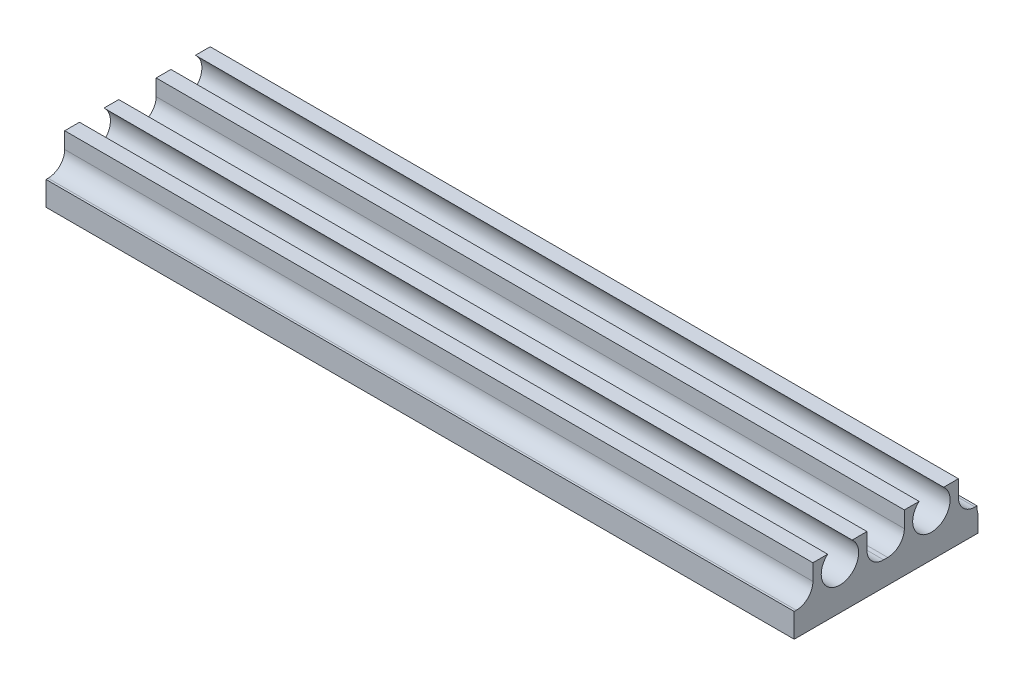
SolidWorks part; units mm, degrees
ref_plane "Спереди" through (0, 0, 0) normal (0, 0, 1) x (1, 0, 0)
ref_plane "Сверху" through (0, 0, 0) normal (0, 1, 0) x (1, 0, 0)
ref_plane "Справа" through (0, 0, 0) normal (1, 0, 0) x (0, 0, -1)
ref_plane "Плоскость4" through (90, 0, 0) normal (1, 0, 0) x (0, 0, -1)
sketch "Эскиз1" plane through (90, 0, 0) normal (1, 0, 0) x (0, 0, -1)
  line L0 (6.75, -24.0938) -> (6.75, 19.25)
  line L1 (6.75, 19.25) -> (-11.5938, 19.25)
  line L2 (-11.5938, 16.75) -> (-11, 16.75)
  line L3 (-11, 16.75) -> (-11, -16.75)
  line L4 (-11, -16.75) -> (-11.5938, -16.75)
  line L5 (-11.5938, -19.25) -> (-11, -19.25)
  line L6 (-11, -19.25) -> (-11, -23.5)
  line L7 (-11, -23.5) -> (-6.75, -23.5)
  line L8 (-6.75, -23.5) -> (-6.75, -24.0938)
  line L9 (-4.25, -24.0938) -> (-4.25, -23.5)
  line L10 (-4.25, -23.5) -> (4.25, -23.5)
  line L11 (4.25, -23.5) -> (4.25, -24.0938)
  arc A0 (-11.5938, 19.25) -> (-11.5938, 16.75) centre (-13.25, 18) ccw
  arc A1 (-11.5938, -16.75) -> (-11.5938, -19.25) centre (-13.25, -18) ccw
  arc A2 (-6.75, -24.0938) -> (-4.25, -24.0938) centre (-5.5, -25.75) ccw
  arc A3 (4.25, -24.0938) -> (6.75, -24.0938) centre (5.5, -25.75) ccw
extrude "Бобышка-Вытянуть1" add sketch "Эскиз1" against normal blind 90
sketch "Эскиз2" plane through (0, 19.25, 0) normal (0, 1, 0) x (-1, 0, 0)
  line L0 (-90, -6.75) -> (-90, 11)
  line L1 (-90, 11) -> (0, 11)
  line L2 (0, 11) -> (0, -6.75)
  line L3 (0, -6.75) -> (-90, -6.75)
extrude "Бобышка-Вытянуть2" add sketch "Эскиз2" along normal blind 8.2
sketch "Эскиз3" plane through (0, 0, -6.75) normal (0, 0, -1) x (-1, 0, 0)
  line L0 (0, -23.5) -> (-90, -23.5)
  line L1 (-90, -23.5) -> (-90, 27.45)
  line L2 (-90, 27.45) -> (0, 27.45)
  line L3 (0, 27.45) -> (0, -23.5)
extrude "Бобышка-Вытянуть3" add sketch "Эскиз3" along normal blind 8.2
sketch "Эскиз4" plane through (0, 0, 0) normal (-1, 0, 0) x (0, 0, 1)
  line L0 (-14.95, -14.75) -> (-11, -14.75)
  line L1 (-11, -14.75) -> (-11, 14.75)
  line L2 (-11, 14.75) -> (-14.95, 14.75)
  line L3 (-14.95, 14.75) -> (-14.95, -14.75)
extrude "Вырез-Вытянуть1" cut sketch "Эскиз4" against normal through all
sketch "Эскиз5" plane through (0, 0, 0) normal (-1, 0, 0) x (0, 0, 1)
  line L0 (-14.95, 27.45) -> (-14.95, 21.25)
  line L1 (-14.95, 21.25) -> (-11, 21.25)
  line L2 (-11, 21.25) -> (-11, 27.45)
  line L3 (-11, 27.45) -> (-14.95, 27.45)
extrude "Вырез-Вытянуть2" cut sketch "Эскиз5" against normal through all
sketch "Эскиз6" plane through (0, 0, 0) normal (-1, 0, 0) x (0, 0, 1)
  line L0 (-11, 27.45) -> (-11, 23.5)
  line L1 (-11, 23.5) -> (-8.75, 23.5)
  line L2 (-8.75, 23.5) -> (-8.75, 27.45)
  line L3 (-8.75, 27.45) -> (-11, 27.45)
extrude "Вырез-Вытянуть3" cut sketch "Эскиз6" against normal through all
sketch "Эскиз7" plane through (0, 0, 0) normal (-1, 0, 0) x (0, 0, 1)
  line L0 (-2.25, 27.45) -> (-2.25, 23.5)
  line L1 (-2.25, 23.5) -> (2.25, 23.5)
  line L2 (2.25, 23.5) -> (2.25, 27.45)
  line L3 (2.25, 27.45) -> (-2.25, 27.45)
extrude "Вырез-Вытянуть4" cut sketch "Эскиз7" against normal through all
sketch "Эскиз8" plane through (0, 0, 0) normal (-1, 0, 0) x (0, 0, 1)
  line L0 (11, 27.45) -> (8.75, 27.45)
  line L1 (8.75, 27.45) -> (8.75, 23.5)
  line L2 (8.75, 23.5) -> (11, 23.5)
  line L3 (11, 23.5) -> (11, 27.45)
extrude "Вырез-Вытянуть5" cut sketch "Эскиз8" against normal through all
sketch "Эскиз9" plane through (0, 0, 0) normal (-1, 0, 0) x (0, 0, 1)
  line L0 (-14.95, -23.5) -> (-11, -23.5)
  line L1 (-11, -23.5) -> (-11, -21.25)
  line L2 (-11, -21.25) -> (-14.95, -21.25)
  line L3 (-14.95, -21.25) -> (-14.95, -23.5)
extrude "Вырез-Вытянуть6" cut sketch "Эскиз9" against normal through all
sketch "Эскиз10" plane through (90, 0, 0) normal (1, 0, 0) x (0, 0, -1)
  line L0 (10.1, 22.6) -> (-10.1, 22.6)
  line L1 (-10.1, 22.6) -> (-10.1, -22.6)
  line L2 (-10.1, -22.6) -> (10.1, -22.6)
  line L3 (10.1, -22.6) -> (10.1, 22.6)
extrude "Вырез-Вытянуть7" cut sketch "Эскиз10" against normal blind 86
hole_wizard "Диаметр отверстия Ø2.5 (2.5)1" positions "Эскиз12" profile "Эскиз11" hole size "Ø2.5" standard "Ansi Metric"
sketch "Эскиз12" plane through (90, 0, 0) normal (1, 0, 0) x (0, 0, -1)
  point P0 (5.5, -25.75)
  point P1 (-13.25, -18)
  point P2 (-5.5, -25.75)
  point P3 (-13.25, 18)
sketch "Эскиз11" plane through (90, -25.75, -5.5) normal (0, 1, 0) x (0, 0, -1)
  line L0 (0, 0) -> (0, 90)
  line L1 (0, 90) -> (1.25, 90)
  line L2 (1.25, 90) -> (1.25, 0)
  line L5 (1.25, 0) -> (0, 0)
  line L11 (0, -6.35) -> (0, 107.95) construction
  dimension "Диаметр сквозного отверстия" = 2.5
  dimension "Глубина сквозного отверстия" = 90
hole_wizard "Диаметр отверстия Ø4.5 (4.5)1" positions "Эскиз14" profile "Эскиз13" hole size "Ø4.5" standard "Ansi Metric"
sketch "Эскиз14" plane through (0, 0, 0) normal (-1, 0, 0) x (0, 0, 1)
  point P0 (-13.25, -18)
  point P1 (-13.25, 18)
  point P2 (-5.5, 25.75)
  point P3 (5.5, 25.75)
sketch "Эскиз13" plane through (0, -18, -13.25) normal (0, 1, 0) x (0, 0, 1)
  line L0 (0, 0) -> (0, 90)
  line L1 (0, 90) -> (2.25, 90)
  line L2 (2.25, 90) -> (2.25, 0)
  line L5 (2.25, 0) -> (0, 0)
  line L11 (0, -6.35) -> (0, 107.95) construction
  dimension "Диаметр сквозного отверстия" = 4.5
  dimension "Глубина сквозного отверстия" = 90
hole_wizard "Диаметр отверстия Ø8.3 (8.3)1" positions "Эскиз16" profile "Эскиз15" hole size "Ø8.3" standard "Ansi Metric"
sketch "Эскиз16" plane through (0, 0, 0) normal (-1, 0, 0) x (0, 0, 1)
  point P0 (0, 0)
sketch "Эскиз15" plane through (0, 0, 0) normal (0, 1, 0) x (0, 0, 1)
  line L0 (0, 0) -> (0, 3.2)
  line L1 (0, 3.2) -> (4.15, 3.2)
  line L2 (4.15, 3.2) -> (4.15, 0)
  line L5 (4.15, 0) -> (0, 0)
  line L10 (0, 3.2) -> (-4.15, 3.2) construction
  line L11 (0, -6.35) -> (0, 107.95) construction
  dimension "Диаметр отверстия" = 8.3
  dimension "Глубина отверстия" = 3.2
  dimension "Угол заточки сверла" = 180
fillet "Скругление1" radius 2 1 edges at (45, 23.5, 8.75)
fillet "Скругление2" radius 2 11 edges at (4, -22.6, 0) (4, 0, -10.1) (4, 0, 10.1) (4, 22.6, 0) (45, -21.25, -11) (45, -14.75, -11) (45, 14.75, -11) (45, 21.25, -11) (45, 23.5, -8.75) (45, 23.5, -2.25) (45, 23.5, 2.25)
sketch "Эскиз17" plane through (90, 0, 0) normal (1, 0, 0) x (0, 0, -1)
  circle A0 centre (5.5, -25.75) radius 1.25 construction
  circle A1 centre (-5.5, -25.75) radius 1.25 construction
  circle A2 centre (-13.25, -18) radius 1.25 construction
  circle A3 centre (-13.25, 18) radius 1.25 construction
  circle A4 centre (5.5, -25.75) radius 1.25
  circle A5 centre (-5.5, -25.75) radius 1.25
  circle A6 centre (-13.25, -18) radius 1.25
  circle A7 centre (-13.25, 18) radius 1.25
extrude "Бобышка-Вытянуть4" add sketch "Эскиз17" against normal blind 90
sketch "Эскиз18" plane through (0, 0, 0) normal (-1, 0, 0) x (0, 0, 1)
  circle A0 centre (0, 0) radius 4.15 construction
  circle A1 centre (0, 0) radius 4.15
extrude "Вырез-Вытянуть8" cut sketch "Эскиз18" against normal blind 100
sketch "Эскиз19" plane through (90, 0, 0) normal (1, 0, 0) x (0, 0, -1)
  line L0 (10.1, 22.6) -> (-10.1, 22.6) construction
  line L1 (10.1, 22.6) -> (-10.1, 22.6)
  line L2 (10.1, 22.6) -> (22.7967, 22.6)
  line L3 (-10.1, 22.6) -> (-23.4112, 22.6)
  line L4 (-23.4112, 22.6) -> (-23.4112, -34.1756)
  line L5 (-23.4112, -34.1756) -> (22.7967, -34.1756)
  line L6 (22.7967, -34.1756) -> (22.7967, 22.6)
extrude "Вырез-Вытянуть9" cut sketch "Эскиз19" against normal blind 130
sketch "Эскиз20" plane through (0, 22.6, 0) normal (0, -1, 0) x (1, 0, 0)
  line L4 (0, -11.1086) -> (90, -11.1086)
  line L5 (90, -11.1086) -> (90, 11)
  line L6 (90, 11) -> (0, 11)
  line L7 (0, 11) -> (0, -11.1086)
  line L8 (0, -11.1086) -> (90, -11.1086)
  line L9 (90, -11.1086) -> (90, 11)
  line L10 (90, 11) -> (0, 11)
  line L11 (0, 11) -> (0, -11.1086)
  dimension "D1" = 0
extrude "Бобышка-Вытянуть5" add sketch "Эскиз20" along normal blind 2
